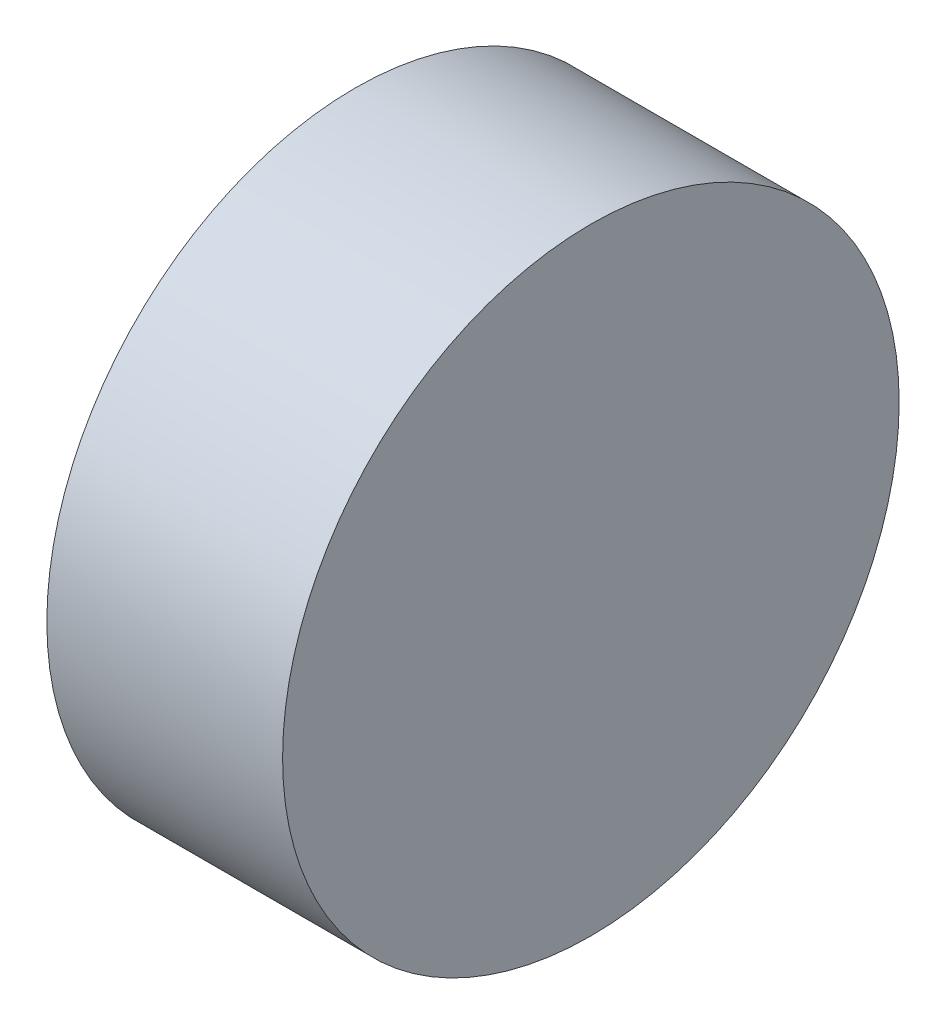
SolidWorks part; units mm, degrees
ref_plane "Plano frontal" through (0, 0, 0) normal (0, 0, 1) x (1, 0, 0)
ref_plane "Plano superior" through (0, 0, 0) normal (0, 1, 0) x (1, 0, 0)
ref_plane "Plano direito" through (0, 0, 0) normal (1, 0, 0) x (0, 0, -1)
sketch "Esboço1" plane through (0, 0, 0) normal (1, 0, 0) x (0, 0, -1)
  circle A0 centre (0, 0) radius 34
  dimension "D1" = 68
extrude "Ressalto-extrusão1" add sketch "Esboço1" along normal blind 26
sketch "Esboço2" plane through (26, 0, 0) normal (1, 0, 0) x (0, 0, -1)
  line L0 (0, 0) -> (-34, 0)
  circle A0 centre (0, 0) radius 34 construction
